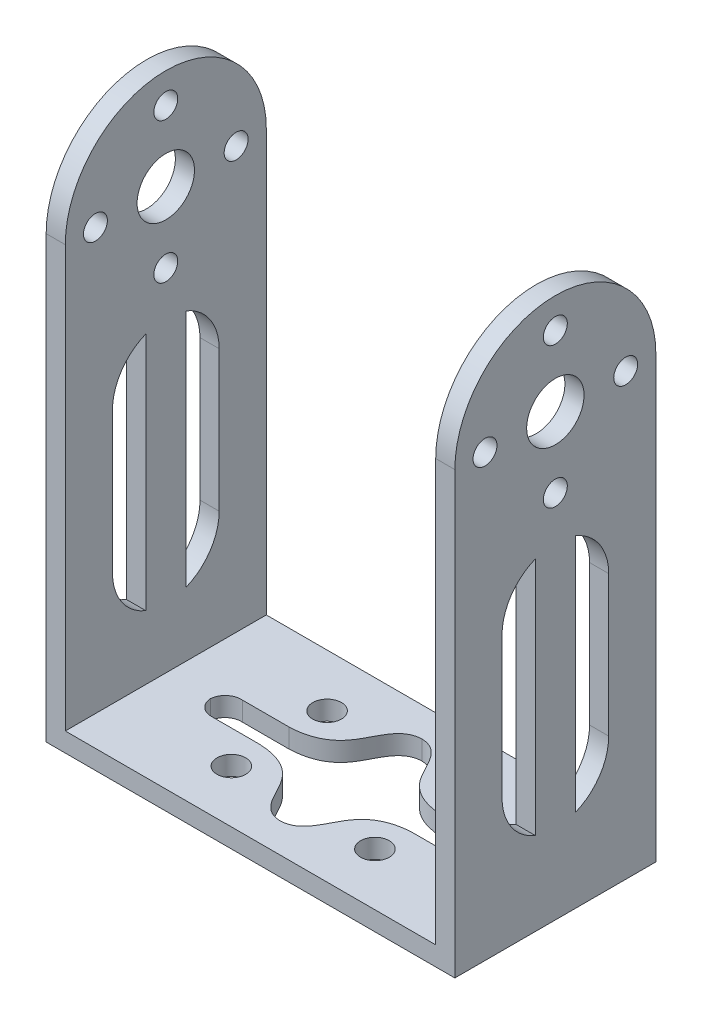
SolidWorks part; units mm, degrees
ref_plane "前视基准面" through (0, 0, 0) normal (0, 0, 1) x (1, 0, 0)
ref_plane "上视基准面" through (0, 0, 0) normal (0, 1, 0) x (1, 0, 0)
ref_plane "右视基准面" through (0, 0, 0) normal (1, 0, 0) x (0, 0, -1)
other "Configuration Table"
sketch "草图1" plane through (0, 0, 0) normal (0, 1, 0) x (1, 0, 0)
  line L0 (0, 10.5) -> (0, -10.5) construction
  line L1 (-21.35, 10.5) -> (21.35, 10.5)
  line L2 (-21.35, 10.5) -> (-21.35, -10.5)
  line L3 (-21.35, -10.5) -> (21.35, -10.5)
  line L4 (21.35, 10.5) -> (21.35, -10.5)
  line L5 (-21.35, 10.5) -> (21.35, -10.5) construction
  line L6 (-21.35, -10.5) -> (21.35, 10.5) construction
  line L7 (-21.35, 0) -> (21.35, 0) construction
  line L8 (8.018, 1.5509) -> (12.9126, 1.5509)
  line L9 (8.018, -1.5509) -> (12.9126, -1.5509)
  line L10 (-8.018, -1.5509) -> (-12.9126, -1.5509)
  line L11 (-8.018, 1.5509) -> (-12.9126, 1.5509)
  circle A0 centre (7.5, 5) radius 1.5
  arc A1 (12.9126, 1.5509) -> (14.6975, 0) centre (13.0296, -0.117) cw
  arc A2 (12.9126, -1.5509) -> (14.6975, 0) centre (13.0296, 0.117) ccw
  circle A3 centre (7.5, -5) radius 1.5
  circle A4 centre (-7.5, -5) radius 1.5
  arc A5 (-12.9126, -1.5509) -> (-14.6975, 0) centre (-13.0296, 0.117) cw
  arc A6 (-12.9126, 1.5509) -> (-14.6975, 0) centre (-13.0296, -0.117) ccw
  circle A7 centre (-7.5, 5) radius 1.5
  spline S0 degree 3 poles (0, 7.4073) (2.0925, 7.358) (3.0437, 2.9519) (6.0077, 1.6267) (8.018, 1.5509) knots 0 0 0 0 0.496823 1 1 1 1
  spline S1 degree 3 poles (0, -7.4073) (2.0925, -7.358) (3.0437, -2.9519) (6.0077, -1.6267) (8.018, -1.5509) knots 0 0 0 0 0.496823 1 1 1 1
  spline S2 degree 3 poles (0, -7.4073) (-2.0925, -7.358) (-3.0437, -2.9519) (-6.0077, -1.6267) (-8.018, -1.5509) knots 0 0 0 0 0.496823 1 1 1 1
  spline S3 degree 3 poles (0, 7.4073) (-2.0925, 7.358) (-3.0437, 2.9519) (-6.0077, 1.6267) (-8.018, 1.5509) knots 0 0 0 0 0.496823 1 1 1 1
  point P0 (0, 0)
  point P6 (7.5, 5)
  point P13 (0, 7.4073)
  point P14 (2.4183, 5.7294)
  point P15 (3.5345, 3.7404)
  point P16 (4.8936, 2.4067)
  point P17 (8.018, 1.5509)
  dimension "D5" = 3
  dimension "D1" = 21
  dimension "D2" = 42.7
  dimension "D3" = 7.5
  dimension "D4" = 5
extrude "凸台-拉伸1" add sketch "草图1" along normal blind 2
sketch "草图2" plane through (-21.35, 0, 0) normal (-1, 0, 0) x (0, 0, 1)
  line L0 (-10.5, 2) -> (-10.5, 46)
  line L1 (10.5, 2) -> (10.5, 46)
  line L2 (-10.5, 46) -> (10.5, 46) construction
  line L3 (0, 46) -> (0, 56.5) construction
  line L4 (-10.5, 2) -> (10.5, 2)
  line L5 (0, 46) -> (0, 38.65) construction
  line L6 (-2.0914, 33.7195) -> (-2.0914, 8.6826)
  line L7 (0, 28.5519) -> (0, 13.8502) construction
  line L8 (5.5747, 28.5519) -> (5.5747, 13.8502)
  line L9 (-5.5747, 28.5519) -> (-5.5747, 13.8502)
  line L10 (2.0914, 33.7195) -> (2.0914, 8.6826)
  arc A0 (-10.5, 46) -> (10.5, 46) centre (0, 46) cw
  circle A1 centre (0, 38.65) radius 1.25
  circle A2 centre (-7.35, 46) radius 1.25
  circle A3 centre (0, 53.35) radius 1.25
  circle A4 centre (7.35, 46) radius 1.25
  circle A5 centre (0, 46) radius 3
  arc A6 (5.5747, 28.5519) -> (2.0914, 33.7195) centre (0, 28.5519) ccw
  arc A7 (-5.5747, 13.8502) -> (-2.0914, 8.6826) centre (0, 13.8502) ccw
  arc A8 (-2.0914, 33.7195) -> (-5.5747, 28.5519) centre (0, 28.5519) ccw
  arc A9 (2.0914, 8.6826) -> (5.5747, 13.8502) centre (0, 13.8502) ccw
  point P12 (-7.35, 46)
  point P13 (7.35, 46)
  point P14 (0, 53.35)
  point P24 (0, 21.201)
  point P29 (-2.0914, 33.7195)
  dimension "D5" = 2.5
  dimension "D9" = 2.5
  dimension "D10" = 2.5
  dimension "D11" = 2.5
  dimension "D12" = 6
  dimension "D1" = 44
  dimension "D2" = 44
  dimension "D3" = 10.5
  dimension "D4" = 7.35
  dimension "D6" = 7.35
  dimension "D7" = 7.35
  dimension "D8" = 7.35
extrude "凸台-拉伸2" add sketch "草图2" against normal blind 2
mirror "镜向1" about plane through (0, 0, 0) normal (1, 0, 0) of "凸台-拉伸2"
